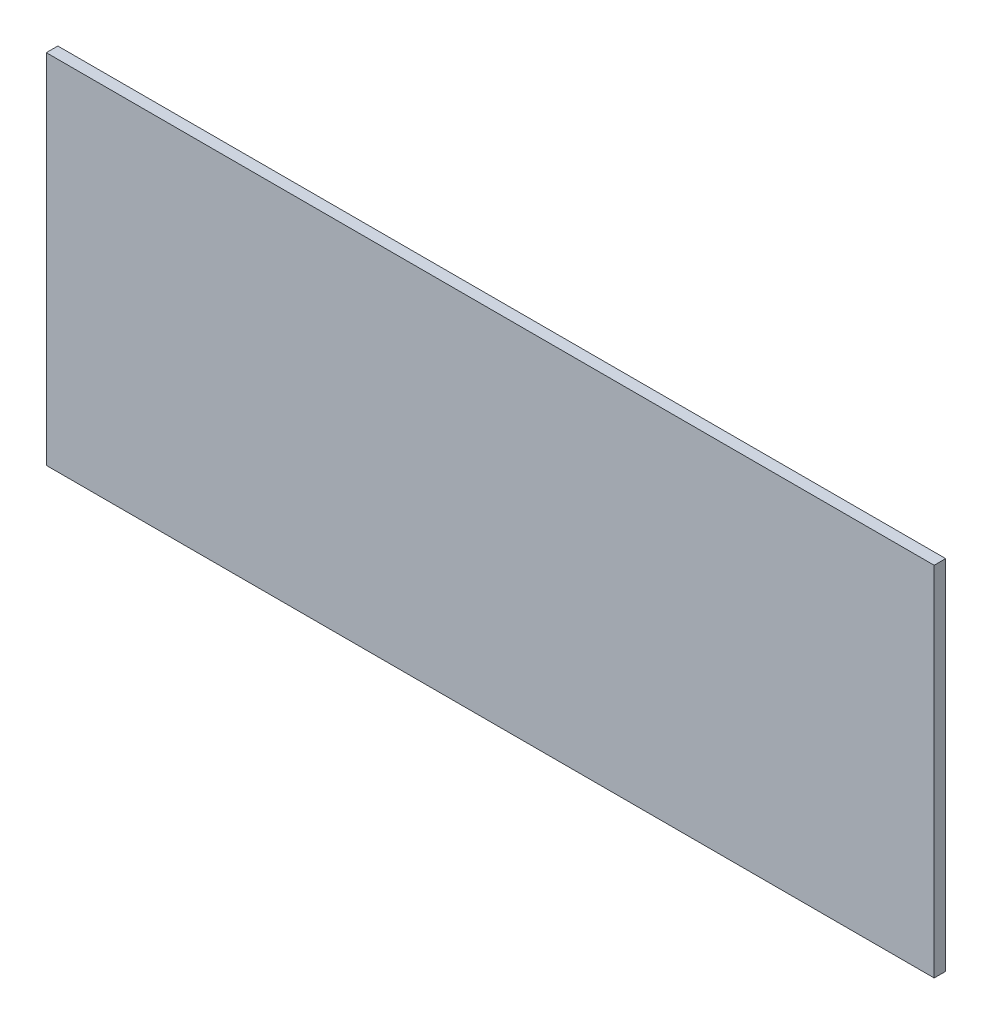
SolidWorks part; units mm, degrees
ref_plane "Front Plane" through (0, 0, 0) normal (0, 0, 1) x (1, 0, 0)
ref_plane "Top Plane" through (0, 0, 0) normal (0, 1, 0) x (1, 0, 0)
ref_plane "Right Plane" through (0, 0, 0) normal (1, 0, 0) x (0, 0, -1)
sketch "Sketch1" plane through (0, 0, 0) normal (0, 0, 1) x (1, 0, 0)
  line L1 (0, 0) -> (154, 0)
  line L2 (0, 0) -> (0, -62)
  line L3 (0, -62) -> (154, -62)
  line L4 (154, 0) -> (154, -62)
  dimension "D1" = 62
  dimension "D2" = 154
extrude "Boss-Extrude1" add sketch "Sketch1" along normal blind 2
